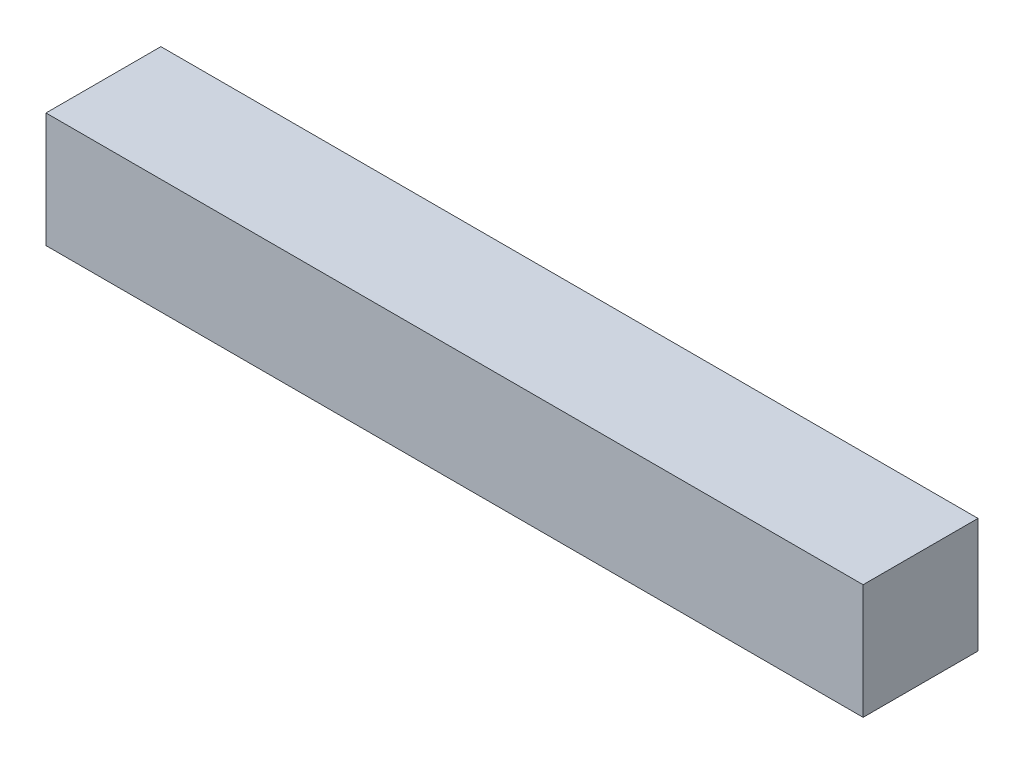
SolidWorks part; units mm, degrees
ref_plane "Front" through (0, 0, 0) normal (0, 0, 1) x (1, 0, 0)
ref_plane "Top" through (0, 0, 0) normal (0, 1, 0) x (1, 0, 0)
ref_plane "Right" through (0, 0, 0) normal (1, 0, 0) x (0, 0, -1)
other "Configuration Table"
sketch "Sketch1" plane through (0, 0, 0) normal (0, 0, 1) x (1, 0, 0)
  line L1 (-12.7, 215.5) -> (-190.5, 215.5)
  line L5 (-190.5, 215.5) -> (-190.5, 190.5)
  line L6 (-12.7, 215.5) -> (-12.7, 190.5)
  line L7 (-12.7, 190.5) -> (-190.5, 190.5)
  dimension "D1" = 25
extrude "Base-Extrude" add sketch "Sketch1" along normal blind 25
